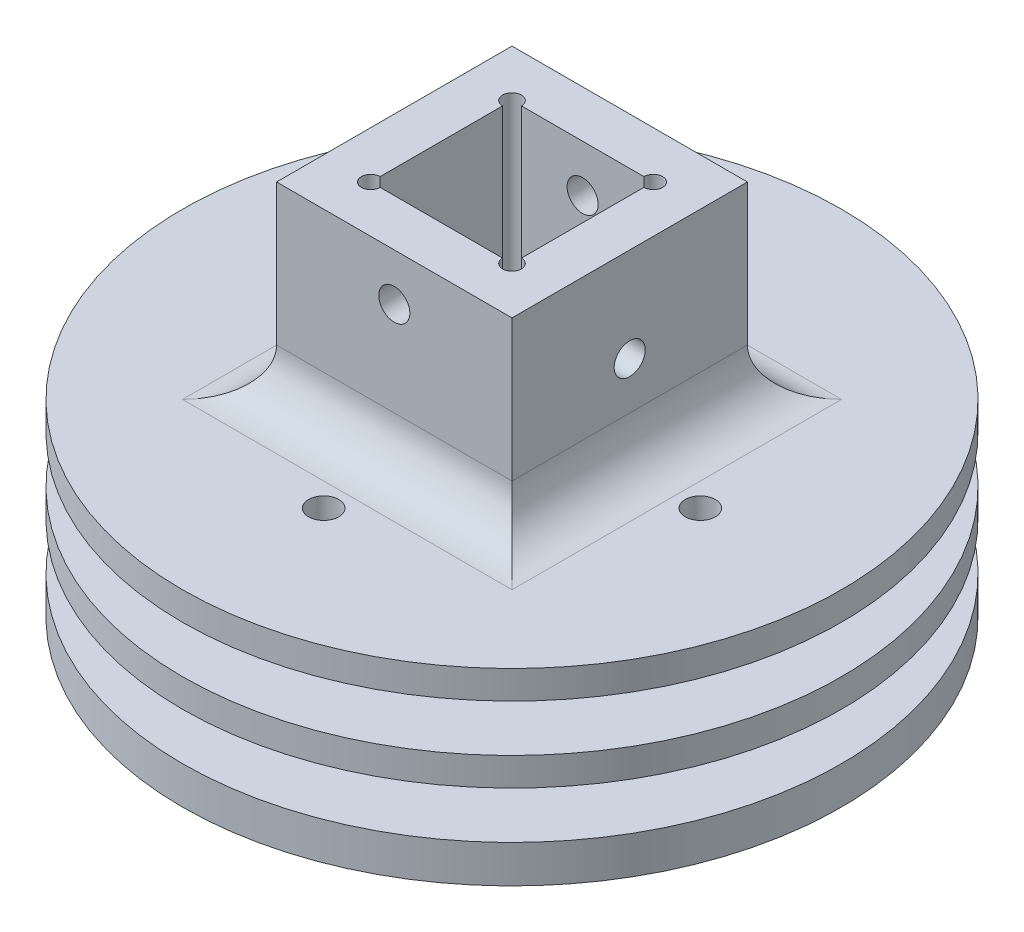
SolidWorks part; units mm, degrees
material "ABS"
ref_plane "前视基准面" through (0, 0, 0) normal (0, 0, 1) x (1, 0, 0)
ref_plane "上视基准面" through (0, 0, 0) normal (0, 1, 0) x (1, 0, 0)
ref_plane "右视基准面" through (0, 0, 0) normal (1, 0, 0) x (0, 0, -1)
other "Configuration Table"
sketch "草图1" plane through (0, 0, 0) normal (0, 1, 0) x (1, 0, 0)
  circle A0 centre (0, 0) radius 35
  dimension "D1" = 70
extrude "凸台-拉伸1" add sketch "草图1" along normal blind 4
sketch "草图2" plane through (0, 4, 0) normal (0, 1, 0) x (1, 0, 0)
  circle A0 centre (0, 0) radius 25
  dimension "D1" = 50
extrude "凸台-拉伸2" add sketch "草图2" along normal blind 5
sketch "草图3" plane through (0, 9, 0) normal (0, 1, 0) x (1, 0, 0)
  circle A0 centre (0, 0) radius 35
  dimension "D1" = 70
extrude "凸台-拉伸3" add sketch "草图3" along normal blind 3
sketch "草图4" plane through (0, 12, 0) normal (0, 1, 0) x (1, 0, 0)
  circle A0 centre (0, 0) radius 25
  dimension "D1" = 50
extrude "凸台-拉伸4" add sketch "草图4" along normal blind 5
sketch "草图5" plane through (0, 17, 0) normal (0, 1, 0) x (1, 0, 0)
  circle A0 centre (0, 0) radius 35
  dimension "D1" = 70
extrude "凸台-拉伸5" add sketch "草图5" along normal blind 3
sketch "草图6" plane through (0, 0, 0) normal (0, -1, 0) x (1, 0, 0)
  line L0 (-33.3462, 0) -> (33.8284, 0) construction
  line L1 (0, 27.467) -> (0, -29.2846) construction
  circle A0 centre (0, 0) radius 20 construction
  circle A1 centre (-20, 0) radius 1.6
  circle A2 centre (0, 20) radius 1.6
  circle A3 centre (0, -20) radius 1.6
  circle A4 centre (20, 0) radius 1.6
  dimension "D1" = 40
  dimension "D2" = 3.2
extrude "切除-拉伸1" cut sketch "草图6" against normal up to next
sketch "草图7" plane through (0, 0, 0) normal (0, -1, 0) x (1, 0, 0)
  circle A0 centre (0, 0) radius 10
  dimension "D1" = 20
extrude "切除-拉伸2" cut sketch "草图7" against normal blind 5
sketch "草图10" plane through (0, 20, 0) normal (0, 1, 0) x (1, 0, 0)
  line L1 (-12.5, -12.5) -> (12.5, -12.5)
  line L2 (-12.5, -12.5) -> (-12.5, 12.5)
  line L3 (-12.5, 12.5) -> (12.5, 12.5)
  line L4 (12.5, -12.5) -> (12.5, 12.5)
  line L5 (-12.5, -12.5) -> (12.5, 12.5) construction
  line L6 (-12.5, 12.5) -> (12.5, -12.5) construction
  line L7 (-7.5, -7.5) -> (7.5, -7.5)
  line L8 (-7.5, -7.5) -> (-7.5, 7.5)
  line L9 (-7.5, 7.5) -> (7.5, 7.5)
  line L10 (7.5, -7.5) -> (7.5, 7.5)
  line L11 (-7.5, -7.5) -> (7.5, 7.5) construction
  line L12 (-7.5, 7.5) -> (7.5, -7.5) construction
  point P0 (0, 0)
  point P2 (0, 0)
  dimension "D1" = 25
  dimension "D2" = 15
extrude "凸台-拉伸6" add sketch "草图10" along normal blind 20
sketch "草图12" plane through (0, 40, 0) normal (0, 1, 0) x (1, 0, 0)
  circle A0 centre (7.5, 7.5) radius 1
  circle A1 centre (-7.5, 7.5) radius 1
  circle A2 centre (-7.5, -7.5) radius 1
  circle A3 centre (7.5, -7.5) radius 1
  dimension "D1" = 2
extrude "切除-拉伸5" cut sketch "草图12" against normal up to surface (20 mm away) up to face at (0, 20, 0)
fillet "圆角1" radius 5 4 edges at (12.5, 20, 0) (0, 20, 12.5) (-12.5, 20, 0) (0, 20, -12.5)
sketch "草图13" plane through (12.5, 0, 0) normal (1, 0, 0) x (0, 0, -1)
  line L0 (0, 72.6693) -> (0, -4.1123) construction
  line L1 (-12.5, 25) -> (12.5, 25) construction
  circle A0 centre (0, 30) radius 1.65
  dimension "D1" = 3.3
  dimension "D2" = 5
extrude "切除-拉伸6" cut sketch "草图13" against normal through all
sketch "草图14" plane through (0, 0, -12.5) normal (0, 0, -1) x (-1, 0, 0)
  line L0 (0, 71.8326) -> (0, -4.3091) construction
  line L1 (-12.5, 25) -> (12.5, 25) construction
  circle A0 centre (0, 35) radius 1.65
  dimension "D1" = 3.3
  dimension "D2" = 10
extrude "切除-拉伸7" cut sketch "草图14" against normal through all
